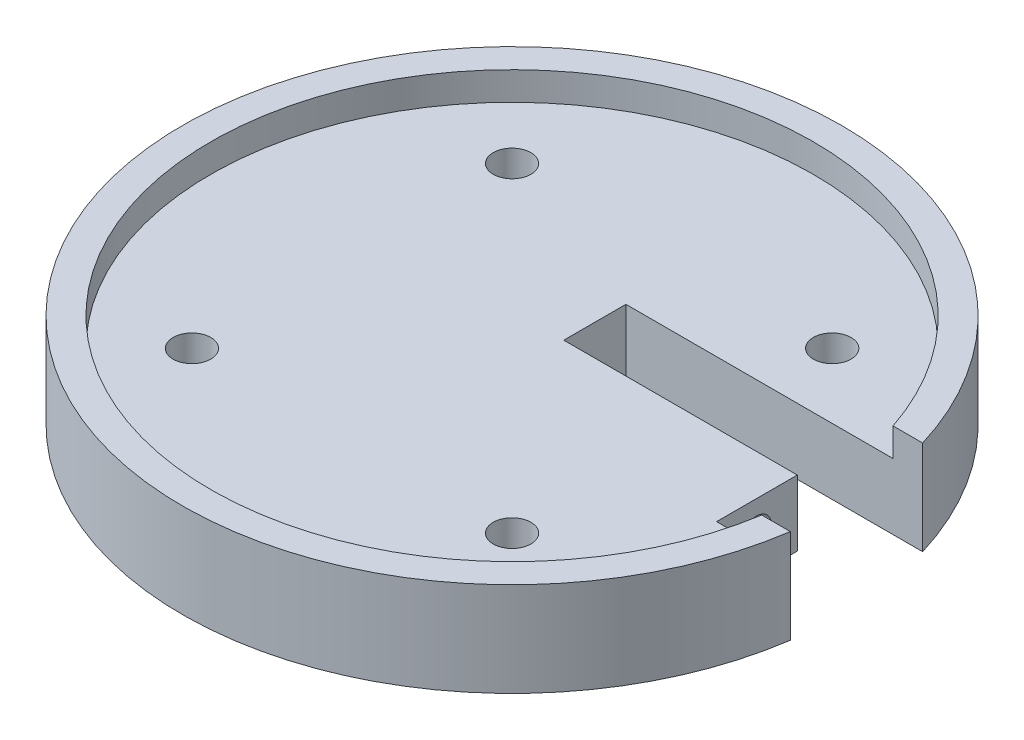
SolidWorks part; units mm, degrees
ref_plane "Front Plane" through (0, 0, 0) normal (0, 0, 1) x (1, 0, 0)
ref_plane "Top Plane" through (0, 0, 0) normal (0, 1, 0) x (1, 0, 0)
ref_plane "Right Plane" through (0, 0, 0) normal (1, 0, 0) x (0, 0, -1)
sketch "Sketch1" plane through (0, 0, 0) normal (0, 1, 0) x (1, 0, 0)
  circle A0 centre (0, 0) radius 35
  dimension "D1" = 70
extrude "Boss-Extrude1" add sketch "Sketch1" along normal blind 10
sketch "Sketch27" plane through (0, 10, 0) normal (0, 1, 0) x (1, 0, 0)
  line L1 (35.2528, 3.4921) -> (26.8023, 3.4921)
  line L2 (35.2528, 3.4921) -> (35.2528, -5.0808)
  line L3 (35.2528, -5.0808) -> (26.8023, -5.0808)
  line L4 (26.8023, 3.4921) -> (26.8023, -5.0808)
  line L5 (35.2528, 3.4921) -> (26.8023, -5.0808) construction
  line L6 (35.2528, -5.0808) -> (26.8023, 3.4921) construction
  point P0 (31.0276, -0.7944)
extrude "Cut-Extrude8" cut sketch "Sketch27" against normal through all
sketch "Sketch28" plane through (0, 10, 0) normal (0, 1, 0) x (1, 0, 0)
sketch "Sketch34" plane through (0, 10, 0) normal (0, 1, 0) x (1, 0, 0)
  circle A0 centre (-17, 17) radius 2
extrude "Cut-Extrude9" cut sketch "Sketch34" against normal through all and the other way through all
sketch "Sketch35" plane through (0, 0, 0) normal (0, -1, 0) x (-1, 0, 0)
  circle A0 centre (-17, 17) radius 2
extrude "Cut-Extrude10" cut sketch "Sketch35" against normal through all
sketch "Sketch36" plane through (0, 0, 0) normal (0, -1, 0) x (-1, 0, 0)
  circle A0 centre (17, -17) radius 2
extrude "Cut-Extrude11" cut sketch "Sketch36" against normal through all
sketch "Sketch37" plane through (0, 0, 0) normal (0, -1, 0) x (1, 0, 0)
  circle A0 centre (17, 17) radius 2
extrude "Cut-Extrude12" cut sketch "Sketch37" against normal through all
sketch "Sketch39" plane through (0, 10, 0) normal (0, 1, 0) x (1, 0, 0)
  circle A0 centre (0, 0) radius 32
extrude "Cut-Extrude14" cut sketch "Sketch39" against normal blind 3
sketch "Sketch40" plane through (26.8023, 0, 0) normal (1, 0, 0) x (0, 0, -1)
  circle A0 centre (-0.8474, 3.8011) radius 1.6
extrude "Cut-Extrude16" cut sketch "Sketch40" against normal blind 35 contours A0
hole_wizard "Ø6.0mm Dowel Hole6" positions "Sketch48" profile "Sketch49" hole size "Ø6.0" standard "DIN"
sketch "Sketch48" plane through (-8.1977, 0, 0) normal (1, 0, 0) x (0, 0, -1)
  point P0 (-0.8474, 3.8011)
sketch "Sketch49" plane through (-8.1977, 3.8011, 0.8474) normal (0, 1, 0) x (0, 0, -1)
  line L0 (0, 0) -> (0, 26.8023)
  line L1 (0, 26.8023) -> (3, 26.8023)
  line L2 (3, 26.8023) -> (3, 0)
  line L5 (3, 0) -> (0, 0)
  line L11 (0, -6.35) -> (0, 107.95) construction
  dimension "Thru Hole Dia." = 6
  dimension "Thru Hole Depth" = 26.8023
sketch "Sketch52" plane through (0, 0, 0) normal (0, -1, 0) x (-1, 0, 0)
  line L0 (-26.8023, 3.4921) -> (-1.9998, 3.4921)
  line L1 (-1.9998, 3.4921) -> (-1.9998, 10.0921)
  line L2 (-1.9998, 10.0921) -> (-33.5134, 10.0921)
  line L3 (-33.5134, 10.0921) -> (-39.472, 10.0921)
  line L4 (-39.472, 10.0921) -> (-42.0193, 10.0921)
  line L5 (-42.0193, 10.0921) -> (-42.0193, 3.4921)
  line L6 (-42.0193, 3.4921) -> (-26.8023, 3.4921)
  arc A0 (-34.6293, -5.0808) -> (-34.8254, 3.4921) centre (0, 0) ccw construction
extrude "Cut-Extrude18" cut sketch "Sketch52" against normal through all
